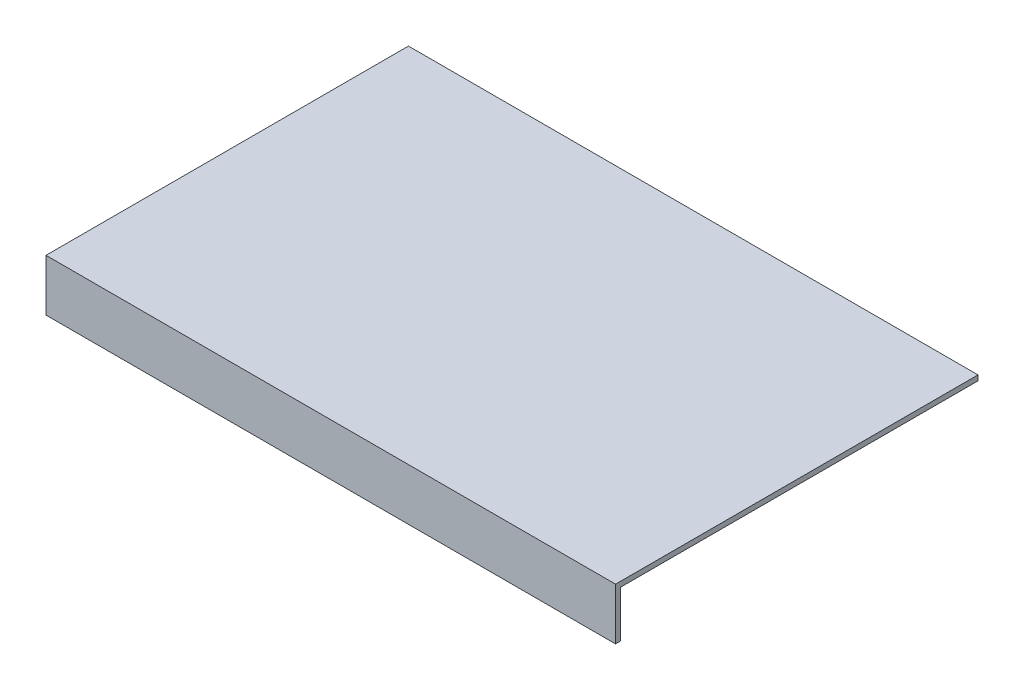
SolidWorks part; units mm, degrees
material "ABS"
ref_plane "Front Plane" through (0, 0, 0) normal (0, 0, 1) x (1, 0, 0)
ref_plane "Top Plane" through (0, 0, 0) normal (0, 1, 0) x (1, 0, 0)
ref_plane "Right Plane" through (0, 0, 0) normal (1, 0, 0) x (0, 0, -1)
sketch "Sketch1" plane through (0, 0, 0) normal (0, 1, 0) x (1, 0, 0)
  line L1 (-279.4, -203.2) -> (279.4, -203.2)
  line L2 (-279.4, -203.2) -> (-279.4, 203.2)
  line L3 (-279.4, 203.2) -> (279.4, 203.2)
  line L4 (279.4, -203.2) -> (279.4, 203.2)
  line L5 (-279.4, -203.2) -> (279.4, 203.2) construction
  line L6 (-279.4, 203.2) -> (279.4, -203.2) construction
  line L7 (-152.4, 203.2) -> (152.4, 203.2)
  line L8 (-152.4, 203.2) -> (-152.4, 12.7)
  line L9 (-152.4, 12.7) -> (152.4, 12.7)
  line L10 (152.4, 203.2) -> (152.4, 12.7)
  point P0 (0, 0)
  dimension "D1" = 558.8
  dimension "D2" = 406.4
  dimension "D3" = 127
  dimension "D4" = 127
  dimension "D5" = 190.5
extrude "Boss-Extrude1" add sketch "Sketch1" along normal blind 25.4 contours L3 L10 L9 L8 L2 L1 L4
fillet "Fillet1" radius 20.32 4 edges at (279.4, 12.7, -203.2) (152.4, 12.7, -203.2) (-279.4, 12.7, -203.2) (-152.4, 12.7, -203.2)
shell "Shell1" thickness 2.54
sketch "Sketch2" plane through (0, 25.4, 0) normal (0, 1, 0) x (1, 0, 0)
  line L0 (-317.2722, 165.1) -> (360.7838, 165.1) construction
  line L1 (-279.4, -203.2) -> (279.4, -203.2) construction
  line L2 (152.4, 182.88) -> (152.4, 12.7) construction
  line L3 (-152.4, 182.88) -> (-152.4, 12.7) construction
  circle A0 centre (-177.72, 165.1) radius 2.54
  circle A1 centre (-167.56, 165.1) radius 2.54
  circle A2 centre (167.56, 165.1) radius 2.54
  circle A3 centre (177.72, 165.1) radius 2.54
  point P12 (157.4, 165.1)
  point P13 (-157.4, 165.1)
  dimension "D2" = 10.16
  dimension "D8" = 5.08
  dimension "D1" = 368.3
  dimension "D3" = 10.16
  dimension "D4" = 10.16
  dimension "D5" = 10.16
  dimension "D6" = 5
  dimension "D7" = 5
extrude "Cut-Extrude1" cut sketch "Sketch2" against normal through all
sketch "Sketch3" plane through (0, 25.4, 0) normal (0, 1, 0) x (1, 0, 0)
  line L0 (-279.4, -25.4) -> (-279.4, 279.1236)
  line L1 (-279.4, -203.2) -> (0, -203.2)
  line L2 (-279.4, -203.2) -> (-279.4, -25.4)
  line L3 (-279.4, -25.4) -> (0, -25.4)
  line L4 (0, -203.2) -> (0, -25.4)
  line L5 (-279.4, 279.1236) -> (306.8498, 279.1236)
  line L6 (306.8498, 279.1236) -> (306.8498, -203.2)
  line L7 (306.8498, -203.2) -> (0, -203.2)
  circle M3 centre (-177.72, 165.1) radius 2.54
  circle M4 centre (-167.56, 165.1) radius 2.54
  circle M5 centre (167.56, 165.1) radius 2.54
  circle M6 centre (177.72, 165.1) radius 2.54
  line M7 (279.4, -203.2) -> (279.4, 182.88)
  arc M8 (279.4, 182.88) -> (259.08, 203.2) centre (259.08, 182.88) ccw
  line M9 (259.08, 203.2) -> (172.72, 203.2)
  arc M10 (172.72, 203.2) -> (152.4, 182.88) centre (172.72, 182.88) ccw
  line M11 (152.4, 182.88) -> (152.4, 12.7)
  line M12 (152.4, 12.7) -> (-152.4, 12.7)
  line M13 (-152.4, 12.7) -> (-152.4, 182.88)
  arc M14 (-152.4, 182.88) -> (-172.72, 203.2) centre (-172.72, 182.88) ccw
  line M15 (-172.72, 203.2) -> (-259.08, 203.2)
  arc M16 (-259.08, 203.2) -> (-279.4, 182.88) centre (-259.08, 182.88) ccw
  line M17 (-279.4, 182.88) -> (-279.4, -203.2)
  line M18 (-279.4, -203.2) -> (279.4, -203.2)
  dimension "D1" = 279.4
  dimension "D2" = 177.8
extrude "Cut-Extrude2" cut sketch "Sketch3" against normal through all contours L4 L3 M18 M7 M8 M9 M10 M11 M12 M13 M14 M15 M16 M17 M4 M6 M5 M3
